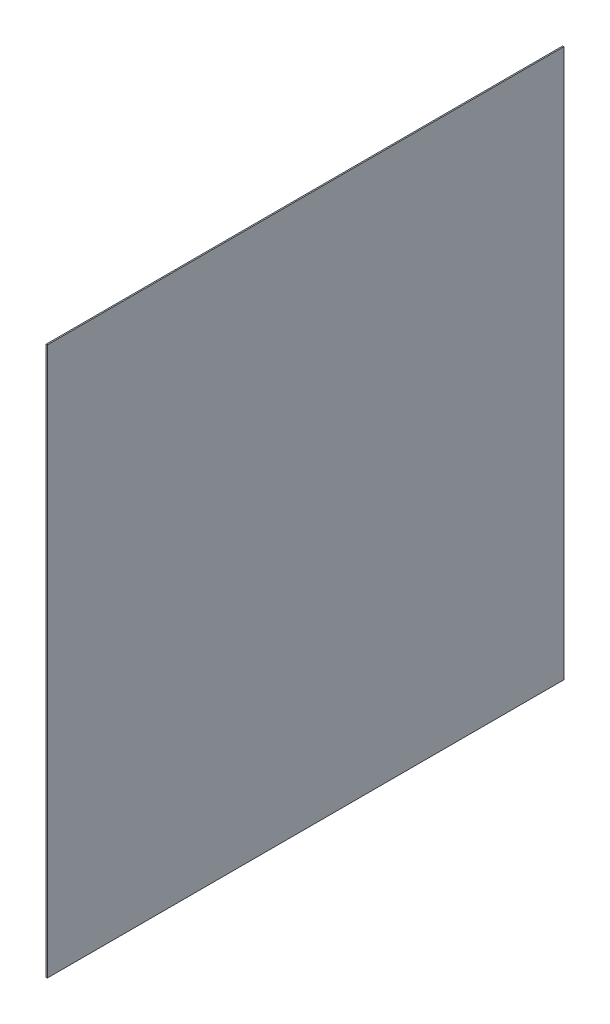
SolidWorks part; units mm, degrees
material "POLYURETHANE (11671)"
ref_plane "Front" through (0, 0, 0) normal (0, 0, 1) x (1, 0, 0)
ref_plane "Top" through (0, 0, 0) normal (0, 1, 0) x (1, 0, 0)
ref_plane "Right" through (0, 0, 0) normal (1, 0, 0) x (0, 0, -1)
sketch "Sketch1" plane through (0, 0, 0) normal (1, 0, 0) x (0, 0, -1)
  line L1 (-1058, 1123.5) -> (1058, 1123.5)
  line L2 (-1058, 1123.5) -> (-1058, -1123.5)
  line L3 (-1058, -1123.5) -> (1058, -1123.5)
  line L4 (1058, 1123.5) -> (1058, -1123.5)
  line L5 (-1058, 1123.5) -> (1058, -1123.5) construction
  line L6 (-1058, -1123.5) -> (1058, 1123.5) construction
  point P0 (0, 0)
  dimension "D1" = 2116
  dimension "D2" = 2247
extrude "Boss-Extrude1" add sketch "Sketch1" along normal blind 5
